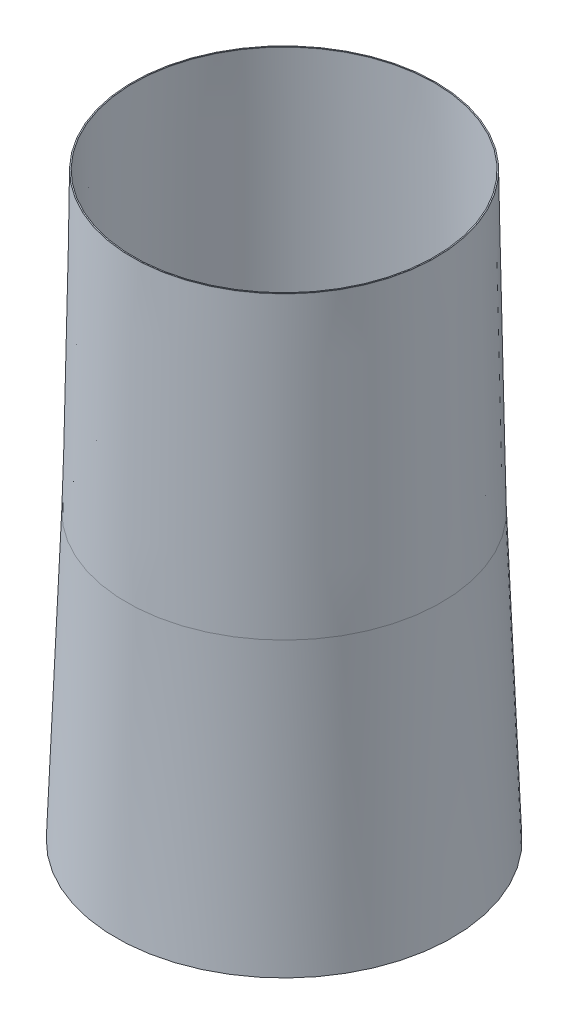
SolidWorks part; units mm, degrees
ref_plane "Přední rovina" through (0, 0, 0) normal (0, 0, 1) x (1, 0, 0)
ref_plane "Horní rovina" through (0, 0, 0) normal (0, 1, 0) x (1, 0, 0)
ref_plane "Pravá rovina" through (0, 0, 0) normal (1, 0, 0) x (0, 0, -1)
sketch "Skica1" plane through (0, 0, 0) normal (0, 0, 1) x (1, 0, 0)
  line L0 (0, 0) -> (0, 289) construction
  line L1 (-14.35, 244.0019) -> (-13.85, 271.0019)
  line L2 (-13.85, 271.0352) -> (-13.75, 271.037)
  line L3 (-15.3498, 218.0058) -> (-15.25, 218)
  line L5 (-14.25, 244) -> (-13.75, 271)
  line L8 (-13.75, 271) -> (-13.75, 271.037) construction
  line L10 (0, 289) -> (-12.25, 289) construction
  arc A0 (-15.3498, 218.0058) -> (-14.35, 244.0019) centre (-667.0714, 256.0893) ccw
  arc A1 (-13.85, 271.0019) -> (-13.85, 271.0352) centre (-14.7498, 271.0185) ccw
  arc A5 (-15.25, 218) -> (-14.25, 244) centre (-667.0714, 256.0893) ccw
  arc A6 (-13.75, 271) -> (-13.75, 271.037) centre (-14.7498, 271.0185) ccw
  dimension "D9" = 14.25
  dimension "D17" = 1
  dimension "D2" = 0.1
  dimension "D10" = 15.25
  dimension "D12" = 13.75
  dimension "D13" = 45
  dimension "D14" = 18
revolve "Rotovat1" add sketch "Skica1" angle 360 about L0
